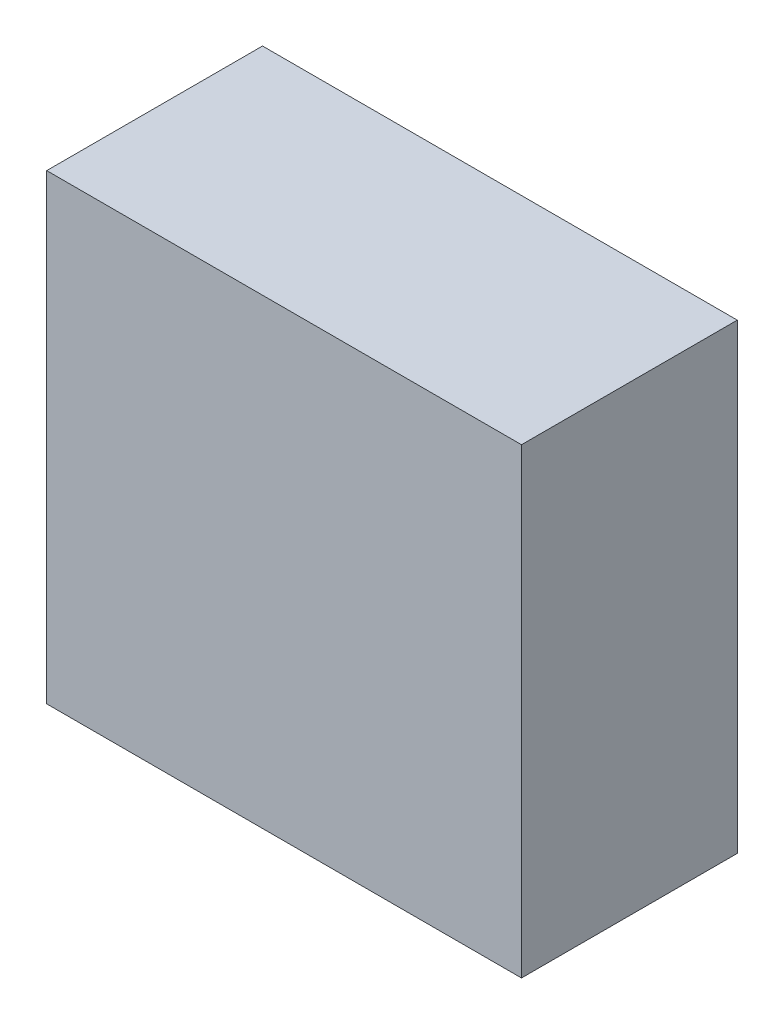
SolidWorks part; units mm, degrees
ref_plane "Front Plane" through (0, 0, 0) normal (0, 0, 1) x (1, 0, 0)
ref_plane "Top Plane" through (0, 0, 0) normal (0, 1, 0) x (1, 0, 0)
ref_plane "Right Plane" through (0, 0, 0) normal (1, 0, 0) x (0, 0, -1)
sketch "Sketch1" plane through (0, 0, 0) normal (0, 1, 0) x (1, 0, 0)
  line L1 (0, 0) -> (27.94, 0)
  line L2 (0, 0) -> (0, 12.7)
  line L3 (0, 12.7) -> (27.94, 12.7)
  line L4 (27.94, 0) -> (27.94, 12.7)
  dimension "D1" = 27.94
  dimension "D2" = 12.7
extrude "Boss-Extrude1" add sketch "Sketch1" along normal blind 27.178
